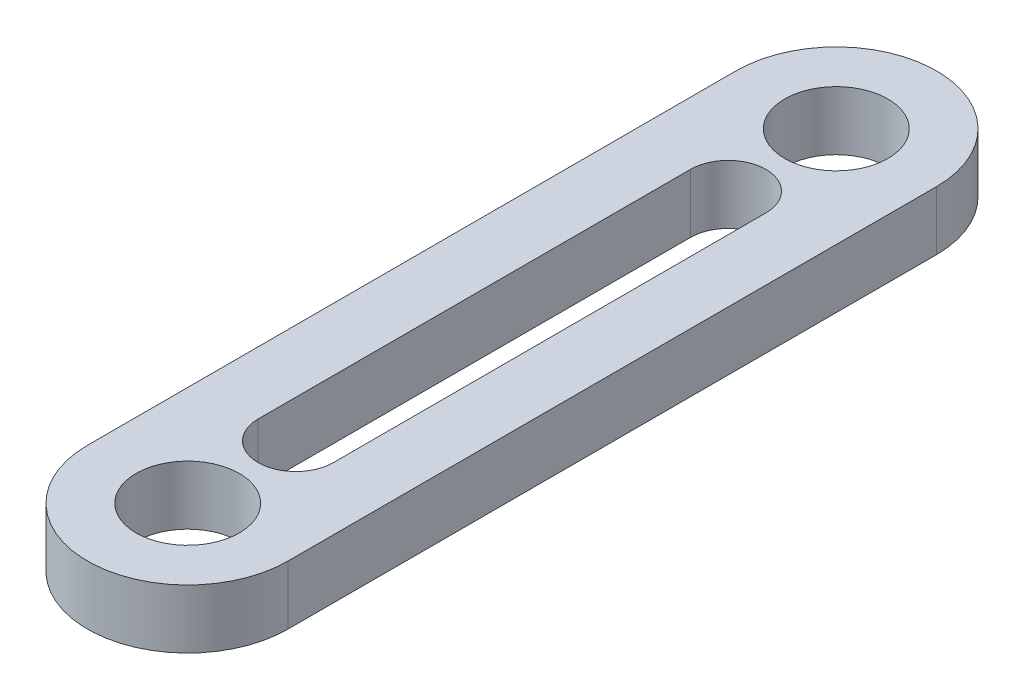
SolidWorks part; units mm, degrees
ref_plane "Front Plane" through (0, 0, 0) normal (0, 0, 1) x (1, 0, 0)
ref_plane "Top Plane" through (0, 0, 0) normal (0, 1, 0) x (1, 0, 0)
ref_plane "Right Plane" through (0, 0, 0) normal (1, 0, 0) x (0, 0, -1)
sketch "Sketch1" plane through (0, 0, 0) normal (0, 1, 0) x (1, 0, 0)
  line L0 (0, 0) -> (0, -110) construction
  line L1 (11, 0) -> (11, -110)
  line L2 (-11, 0) -> (-11, -110)
  line L3 (17, 0) -> (17, -110)
  line L4 (-17, 0) -> (-17, -110)
  line L5 (0, -91.6667) -> (0, -18.3333) construction
  line L6 (-6.3961, -91.6667) -> (-6.3961, -18.3333)
  line L7 (6.3961, -91.6667) -> (6.3961, -18.3333)
  arc A0 (11, 0) -> (-11, 0) centre (0, 0) ccw
  arc A1 (-11, -110) -> (11, -110) centre (0, -110) ccw
  arc A2 (-17, -110) -> (17, -110) centre (0, -110) ccw
  arc A3 (17, 0) -> (-17, 0) centre (0, 0) ccw
  circle A4 centre (0, 0) radius 11 construction
  circle A5 centre (0, -110) radius 11 construction
  arc A6 (-6.3961, -91.6667) -> (6.3961, -91.6667) centre (0, -91.6667) ccw
  arc A7 (6.3961, -18.3333) -> (-6.3961, -18.3333) centre (0, -18.3333) ccw
  point P3 (0, -55)
  point P20 (0, -55)
  dimension "D1" = 22
  dimension "D2" = 110
  dimension "D4" = 12.7922
  dimension "D5" = 73.3333
  dimension "D3" = 6
extrude "Boss-Extrude1" add sketch "Sketch1" along normal blind 10 contours L3 A3 L4 A2 A1 L2 A0 L1 | A5 L1 A4 L2 A7 L7 A6 L6
hole_wizard "M16 Clearance Hole1" positions "3DSketch2" profile "Sketch3" hole size "M16" standard "ANSI Metric" end condition through all
sketch3d "3DSketch2"
  point P0 (0, 10, 110)
  point P2 (0, 0, 0)
  point P5 (0, 10, 0)
sketch "Sketch3" plane through (0, 10, 110) normal (1, 0, 0) x (0, 0, 1)
  line L0 (0, 0) -> (0, 10)
  line L1 (0, 10) -> (8.75, 10)
  line L2 (8.75, 10) -> (8.75, 0)
  line L5 (8.75, 0) -> (0, 0)
  line L11 (0, -6.35) -> (0, 107.95) construction
  dimension "Thru Hole Dia." = 17.5
  dimension "Thru Hole Depth" = 10
equation "\"len\"= 110"
equation "\"D2@Sketch1\"=\"len\""
equation "\"D5@Sketch1\"=\"len\"/1.5"
